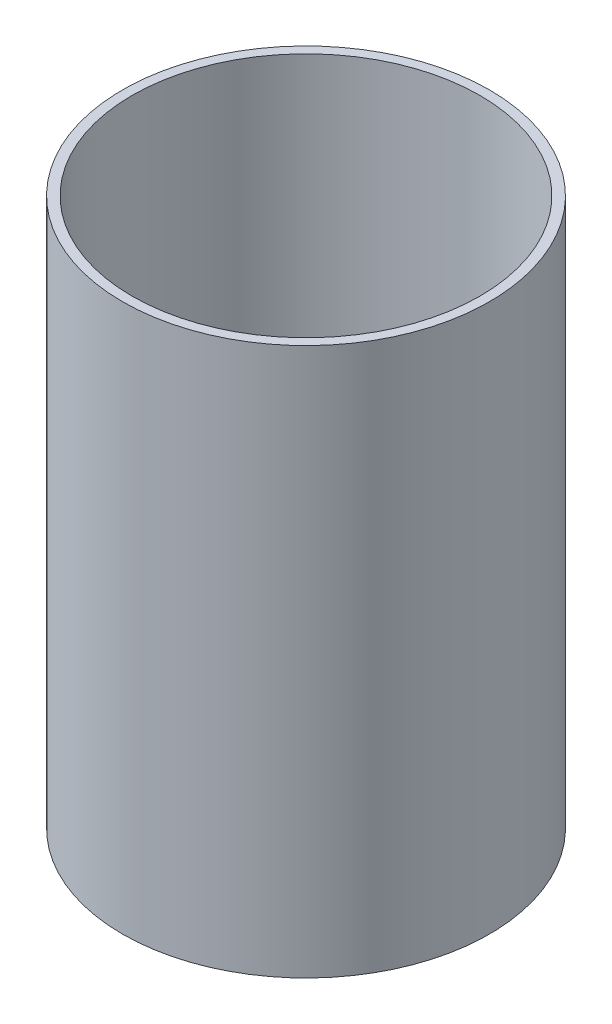
SolidWorks part; units mm, degrees
material "Chrome Stainless Steel"
ref_plane "Front Plane" through (0, 0, 0) normal (0, 0, 1) x (1, 0, 0)
ref_plane "Top Plane" through (0, 0, 0) normal (0, 1, 0) x (1, 0, 0)
ref_plane "Right Plane" through (0, 0, 0) normal (1, 0, 0) x (0, 0, -1)
sketch "Sketch1" plane through (0, 0, 0) normal (0, 1, 0) x (1, 0, 0)
  circle A0 centre (0, 0) radius 33.5
  dimension "D1" = 67
extrude "Boss-Extrude1" add sketch "Sketch1" along normal blind 100
sketch "Sketch2" plane through (0, 100, 0) normal (0, 1, 0) x (1, 0, 0)
  circle A0 centre (0, 0) radius 31.75
  circle A1 centre (0, 0) radius 33.5 construction
  dimension "D1" = 1.75
extrude "Cut-Extrude1" cut sketch "Sketch2" against normal blind 98
